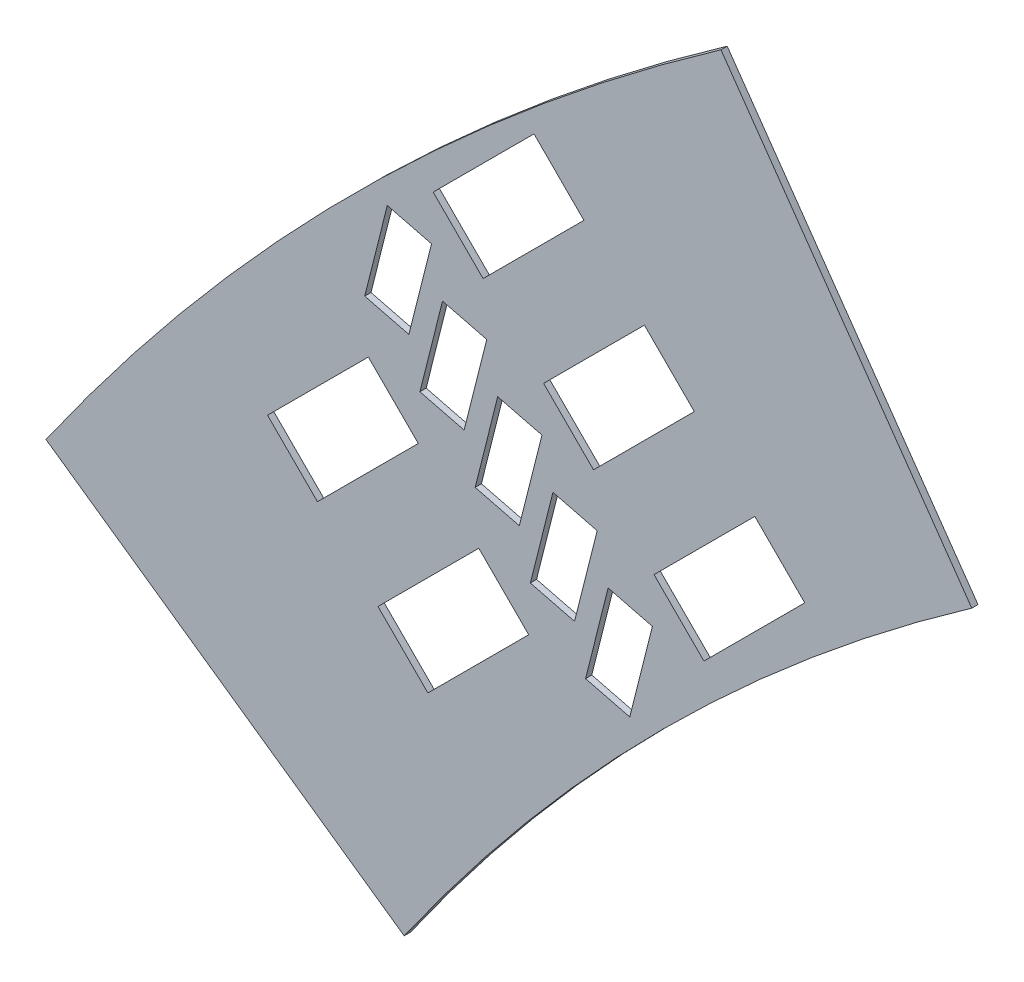
SolidWorks part; units mm, degrees
material "ABS"
ref_plane "Front Plane" through (0, 0, 0) normal (1, 0, 0) x (0, 1, 0)
ref_plane "Top Plane" through (0, 0, 0) normal (0, 0, 1) x (0, 1, 0)
ref_plane "Right Plane" through (0, 0, 0) normal (0, 1, 0) x (-1, 0, 0)
sketch "Sketch1" plane through (0, 0, 0) normal (0, 0, 1) x (0, 1, 0)
  line L0 (50.4747, 72.0854) -> (42.4447, 60.6173)
  line L1 (60.6173, 42.4447) -> (72.0854, 50.4747)
  line L2 (0, 0) -> (0, 88) construction
  line L3 (0, 0) -> (50.4747, 72.0854) construction
  line L4 (0, 0) -> (88, 0) construction
  line L5 (0, 0) -> (72.0854, 50.4747) construction
  arc A0 (72.0854, 50.4747) -> (50.4747, 72.0854) centre (0, 0) ccw
  arc A1 (60.6173, 42.4447) -> (42.4447, 60.6173) centre (0, 0) ccw
  arc A2 (42.4447, 60.6173) -> (60.6173, 42.4447) centre (0, 0) ccw construction
  arc A3 (50.4747, 72.0854) -> (72.0854, 50.4747) centre (0, 0) ccw construction
  dimension "D1" = 176
  dimension "D2" = 14
  dimension "D3" = 35
  dimension "D4" = 35
extrude "Boss-Extrude1" add sketch "Sketch1" along normal mid plane 0.2
sketch "Sketch2" plane through (0, 0, 0.1) normal (0, 0, 1) x (1, 0, 0)
  line L0 (0, 0) -> (-62.2254, 62.2254) construction
  line L1 (-54.624, 54.2704) -> (-53.2098, 52.8562) construction
  line L2 (-54.624, 54.2704) -> (-54.2704, 54.624) construction
  line L3 (-53.2098, 52.8562) -> (-52.8562, 53.2098) construction
  line L4 (-54.2704, 54.624) -> (-52.8562, 53.2098) construction
  line L5 (-54.624, 54.2704) -> (-52.8562, 53.2098) construction
  line L6 (-53.2098, 52.8562) -> (-54.2704, 54.624) construction
  line L7 (-53.7401, 53.7401) -> (-54.4472, 54.4472) construction
  line L8 (-56.3918, 56.0382) -> (-54.9776, 54.624) construction
  line L9 (-54.9776, 54.624) -> (-54.624, 54.9776) construction
  line L10 (-56.0382, 56.3918) -> (-54.624, 54.9776) construction
  line L11 (-56.3918, 56.0382) -> (-56.0382, 56.3918) construction
  line L12 (-58.1595, 57.806) -> (-56.7453, 56.3918) construction
  line L13 (-56.7453, 56.3918) -> (-56.3918, 56.7453) construction
  line L14 (-57.806, 58.1595) -> (-56.3918, 56.7453) construction
  line L15 (-58.1595, 57.806) -> (-57.806, 58.1595) construction
  line L16 (-59.9273, 59.5737) -> (-58.5131, 58.1595) construction
  line L17 (-58.5131, 58.1595) -> (-58.1595, 58.5131) construction
  line L18 (-59.5737, 59.9273) -> (-58.1595, 58.5131) construction
  line L19 (-59.9273, 59.5737) -> (-59.5737, 59.9273) construction
  line L20 (-61.6951, 61.3415) -> (-60.2809, 59.9273) construction
  line L21 (-60.2809, 59.9273) -> (-59.9273, 60.2809) construction
  line L22 (-61.3415, 61.6951) -> (-59.9273, 60.2809) construction
  line L23 (-61.6951, 61.3415) -> (-61.3415, 61.6951) construction
  line L24 (-54.8098, 52.4806) -> (-54.0863, 55.3559)
  line L25 (-54.8098, 52.4806) -> (-53.394, 52.1243)
  line L26 (-54.0863, 55.3559) -> (-52.6704, 54.9996)
  line L27 (-53.394, 52.1243) -> (-52.6704, 54.9996)
  line L28 (-54.8098, 52.4806) -> (-52.6704, 54.9996) construction
  line L29 (-54.0863, 55.3559) -> (-53.394, 52.1243) construction
  line L30 (-56.5776, 54.2484) -> (-55.854, 57.1237)
  line L31 (-56.5776, 54.2484) -> (-55.1617, 53.8921)
  line L32 (-55.1617, 53.8921) -> (-54.4382, 56.7674)
  line L33 (-55.854, 57.1237) -> (-54.4382, 56.7674)
  line L34 (-58.3454, 56.0161) -> (-57.6218, 58.8915)
  line L35 (-58.3454, 56.0161) -> (-56.9295, 55.6598)
  line L36 (-56.9295, 55.6598) -> (-56.2059, 58.5352)
  line L37 (-57.6218, 58.8915) -> (-56.2059, 58.5352)
  line L38 (-60.1131, 57.7839) -> (-59.3896, 60.6592)
  line L39 (-60.1131, 57.7839) -> (-58.6973, 57.4276)
  line L40 (-58.6973, 57.4276) -> (-57.9737, 60.3029)
  line L41 (-59.3896, 60.6592) -> (-57.9737, 60.3029)
  line L42 (-61.8809, 59.5517) -> (-61.1573, 62.427)
  line L43 (-61.8809, 59.5517) -> (-60.465, 59.1954)
  line L44 (-60.465, 59.1954) -> (-59.7415, 62.0707)
  line L45 (-61.1573, 62.427) -> (-59.7415, 62.0707)
  line L46 (-53.7401, 53.7401) -> (-50.2046, 57.2756) construction
  line L47 (-51.0195, 54.8626) -> (-52.6176, 56.4607)
  line L48 (-51.0195, 54.8626) -> (-47.7916, 58.0906)
  line L49 (-52.6176, 56.4607) -> (-49.3896, 59.6887)
  line L50 (-47.7916, 58.0906) -> (-49.3896, 59.6887)
  line L51 (-51.0195, 54.8626) -> (-49.3896, 59.6887) construction
  line L52 (-52.6176, 56.4607) -> (-47.7916, 58.0906) construction
  line L53 (-55.5079, 55.5079) -> (-59.0434, 51.9723) construction
  line L54 (-59.8584, 49.5593) -> (-56.6304, 52.7873)
  line L55 (-59.8584, 49.5593) -> (-61.4564, 51.1574)
  line L56 (-56.6304, 52.7873) -> (-58.2285, 54.3854)
  line L57 (-61.4564, 51.1574) -> (-58.2285, 54.3854)
  line L58 (-59.8584, 49.5593) -> (-58.2285, 54.3854) construction
  line L59 (-56.6304, 52.7873) -> (-61.4564, 51.1574) construction
  line L60 (-54.5551, 58.3982) -> (-56.1531, 59.9962)
  line L61 (-54.5551, 58.3982) -> (-51.3271, 61.6261)
  line L62 (-51.3271, 61.6261) -> (-52.9252, 63.2242)
  line L63 (-56.1531, 59.9962) -> (-52.9252, 63.2242)
  line L64 (-58.0906, 61.9337) -> (-59.6887, 63.5318)
  line L65 (-58.0906, 61.9337) -> (-54.8626, 65.1617)
  line L66 (-54.8626, 65.1617) -> (-56.4607, 66.7597)
  line L67 (-59.6887, 63.5318) -> (-56.4607, 66.7597)
  line L68 (-63.3939, 53.0949) -> (-60.1659, 56.3228)
  line L69 (-63.3939, 53.0949) -> (-64.992, 54.6929)
  line L70 (-64.992, 54.6929) -> (-61.764, 57.9209)
  line L71 (-60.1659, 56.3228) -> (-61.764, 57.9209)
  arc A0 (-50.4747, 72.0854) -> (-72.0854, 50.4747) centre (0, 0) ccw construction
  circle A1 centre (0, 0) radius 75 construction
  point P8 (-53.7401, 53.7401)
  point P10 (-55.5079, 55.5079)
  point P21 (-57.2756, 57.2756)
  point P26 (-59.0434, 59.0434)
  point P31 (-60.8112, 60.8112)
  dimension "D1" = 13
  dimension "D2" = 0.5
  dimension "D3" = 2
  dimension "D5" = 2.5
  dimension "D6" = 1.46
  dimension "D7" = 2.965
  dimension "D8" = 4.565
  dimension "D9" = 2.26
  dimension "D10" = 5
  dimension "D11" = 1.0705
  dimension "D13" = 5
  dimension "D15" = 5
  dimension "D4" = 5
  dimension "D12" = 3
  dimension "D14" = 2
extrude "Cut-Extrude1" cut sketch "Sketch2" against normal through all
equation "\"D4@Sketch1\"=\"D3@Sketch1\""
equation "\"D13@Sketch2\"=2 * \"D5@Sketch2\""
equation "\"D15@Sketch2\"=\"D13@Sketch2\""
